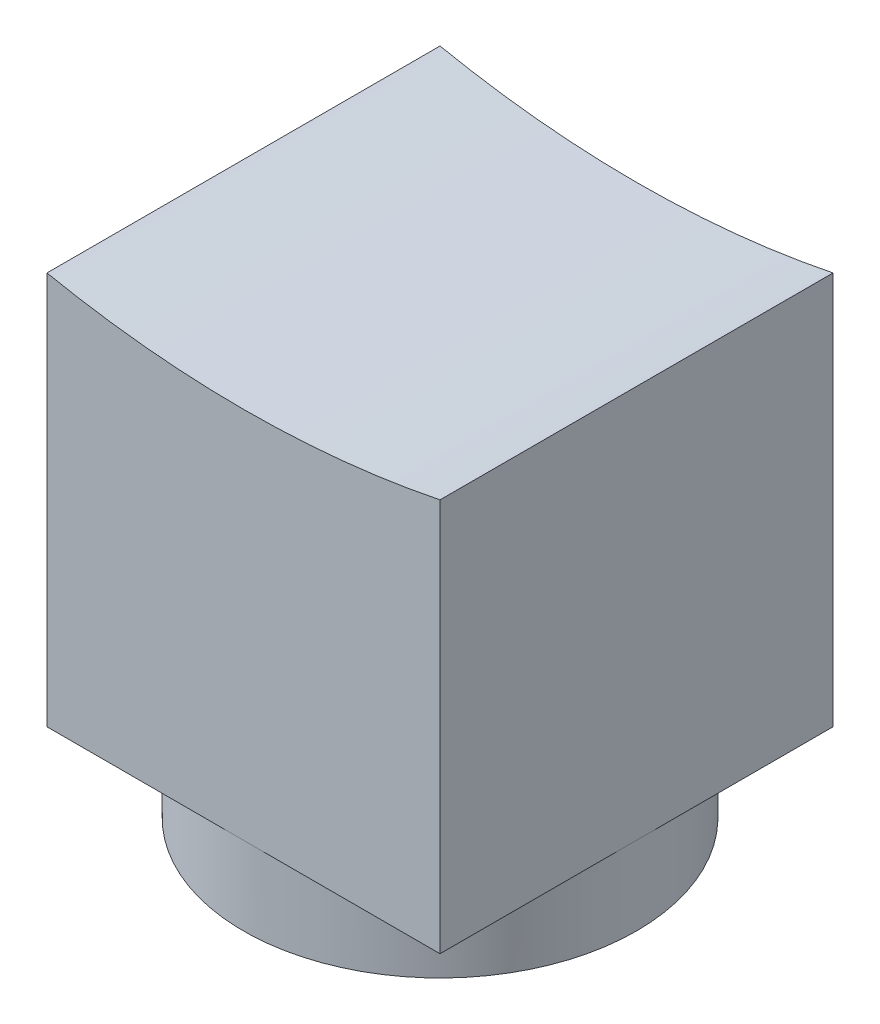
SolidWorks part; units mm, degrees
ref_plane "Front Plane" through (0, 0, 0) normal (0, 0, 1) x (1, 0, 0)
ref_plane "Top Plane" through (0, 0, 0) normal (0, 1, 0) x (1, 0, 0)
ref_plane "Right Plane" through (0, 0, 0) normal (1, 0, 0) x (0, 0, -1)
sketch "Sketch1" plane through (0, 0, 0) normal (0, 0, 1) x (1, 0, 0)
  line L2 (25, 25) -> (25, -25)
  line L3 (25, -25) -> (-25, -25)
  line L4 (-25, 25) -> (-25, -25)
  arc A0 (-25, 25) -> (25, 25) centre (0, 147.4684) ccw
  point P0 (0, 0)
  dimension "D5" = 249.988
  dimension "D1" = 50
  dimension "D2" = 50
  dimension "D3" = 25
  dimension "D4" = 50
extrude "Boss-Extrude1" add sketch "Sketch1" along normal blind 50
sketch "Sketch2" plane through (0, -25, 0) normal (0, -1, 0) x (1, 0, 0)
  circle A0 centre (0, 25) radius 25
  dimension "D1" = 25
extrude "Boss-Extrude2" add sketch "Sketch2" along normal blind 10
equation "\"ThrusterDim\"= 140mm"
equation "\"hatchHoleDiameter\"= 600mm"
equation "\"hullThickness\"= 120mm"
equation "\"gasketHullInterconnectWidth\"= 100mm"
equation "\"collarThickness\"= 15"
equation "\"hatchTunnelLength\"=200"
equation "\"oRingDiameter\"=2"
equation "\"boltPatternRadiusInterconnect\"=500"
equation "\"interconnectBoltDiameter\"=30"
equation "\"hatchShaftDiameter\"=20"
equation "\"hatchMinima\"=50"
equation "\"hullDiameter\"=2000"
equation "\"hatchMaxima\"=180"
equation "\"bushingFlatHatch\"=15"
equation "\"hingePivotDiameter\"=20"
equation "\"handleWidth\"=250"
equation "\"handleHeight\"=160"
equation "\"handleThickness\"=25"
equation "\"FrameLength\"= 4300"
equation "\"FrameMidLength\"= 3000"
equation "\"TubeOD\"= 100"
equation "\"FrameBackFlat\"= 800"
equation "\"TubeWall\"=15"
equation "\"TopMemberAngle\"=120"
equation "\"FrameHight\"= 2500"
equation "\"D5@Sketch1\"=\"ThrusterDim\" *2 *0.8571+10"
